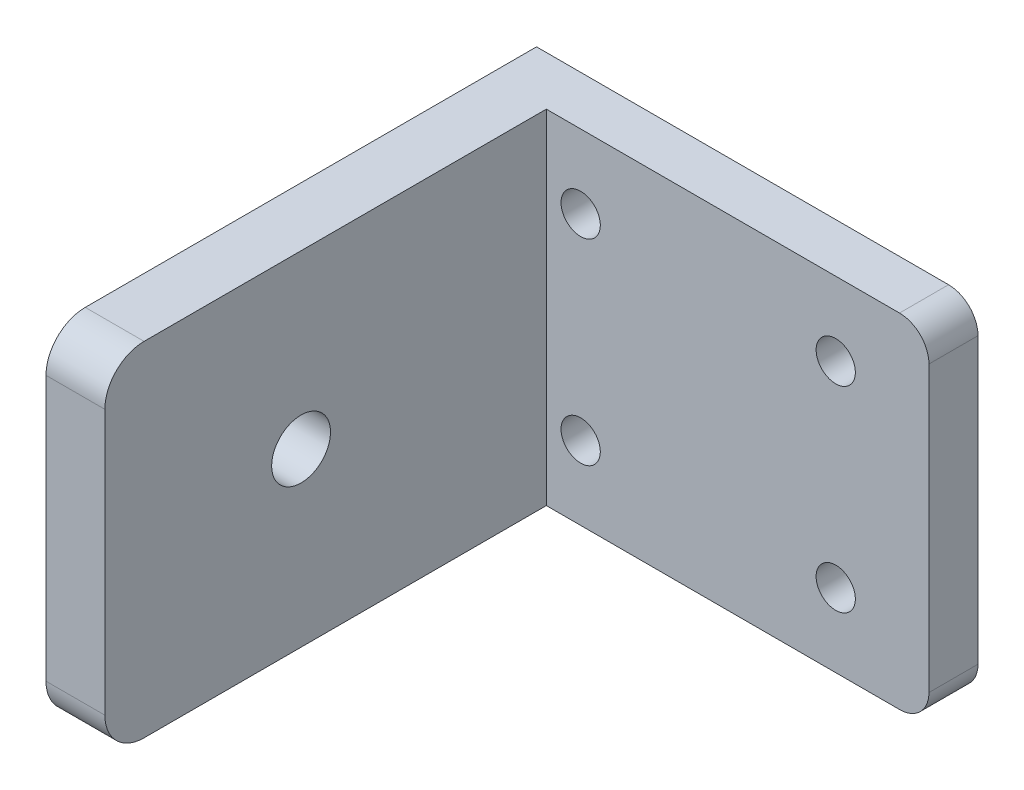
SolidWorks part; units mm, degrees
ref_plane "前视基准面" through (0, 0, 0) normal (0, 0, 1) x (1, 0, 0)
ref_plane "上视基准面" through (0, 0, 0) normal (0, 1, 0) x (1, 0, 0)
ref_plane "右视基准面" through (0, 0, 0) normal (1, 0, 0) x (0, 0, -1)
other "Configuration Table"
sketch "草图1" plane through (0, 0, 0) normal (0, 0, 1) x (1, 0, 0)
  line L1 (-22.5, -17.5) -> (22.5, -17.5)
  line L2 (-22.5, -17.5) -> (-22.5, 17.5)
  line L3 (-22.5, 17.5) -> (22.5, 17.5)
  line L4 (22.5, -17.5) -> (22.5, 17.5)
  line L5 (-22.5, -17.5) -> (22.5, 17.5) construction
  line L6 (-22.5, 17.5) -> (22.5, -17.5) construction
  point P0 (0, 0)
  dimension "D1" = 35
  dimension "D2" = 45
extrude "凸台-拉伸1" add sketch "草图1" along normal blind 5
sketch "草图2" plane through (0, 0, 5) normal (0, 0, 1) x (1, 0, 0)
  line L0 (-22.5, -17.5) -> (22.5, -17.5) construction
  line L1 (-22.5, 17.5) -> (-16.5, 17.5)
  line L2 (-22.5, 17.5) -> (-22.5, -17.5)
  line L3 (-22.5, -17.5) -> (-16.5, -17.5)
  line L4 (-16.5, 17.5) -> (-16.5, -17.5)
  dimension "D1" = 6
extrude "凸台-拉伸2" add sketch "草图2" along normal blind 45
sketch "草图3" plane through (-22.5, 0, 0) normal (-1, 0, 0) x (0, 0, 1)
  line L0 (50, 17.5) -> (50, -17.5) construction
  circle A0 centre (30, 0) radius 3
  dimension "D1" = 6
  dimension "D2" = 20
extrude "切除-拉伸1" cut sketch "草图3" against normal through all
fillet "圆角1" radius 3 2 edges at (22.5, -17.5, 2.5) (22.5, 17.5, 2.5)
fillet "圆角2" radius 4 2 edges at (-19.5, -17.5, 50) (-19.5, 17.5, 50)
sketch "草图4" plane through (0, 0, 0) normal (0, 0, -1) x (-1, 0, 0)
  line L1 (-13, -10) -> (13, -10)
  line L2 (-13, -10) -> (-13, 10)
  line L3 (-13, 10) -> (13, 10)
  line L4 (13, -10) -> (13, 10)
  line L5 (-13, -10) -> (13, 10) construction
  line L6 (-13, 10) -> (13, -10) construction
  circle A0 centre (-13, 10) radius 2
  circle A1 centre (13, 10) radius 2
  circle A2 centre (13, -10) radius 2
  circle A3 centre (-13, -10) radius 2
  point P0 (0, 0)
  dimension "D3" = 4
  dimension "D4" = 4
  dimension "D5" = 4
  dimension "D6" = 4
  dimension "D1" = 20
  dimension "D2" = 26
extrude "切除-拉伸2" cut sketch "草图4" against normal up to next contours A0 | A1 | A3 | A2
